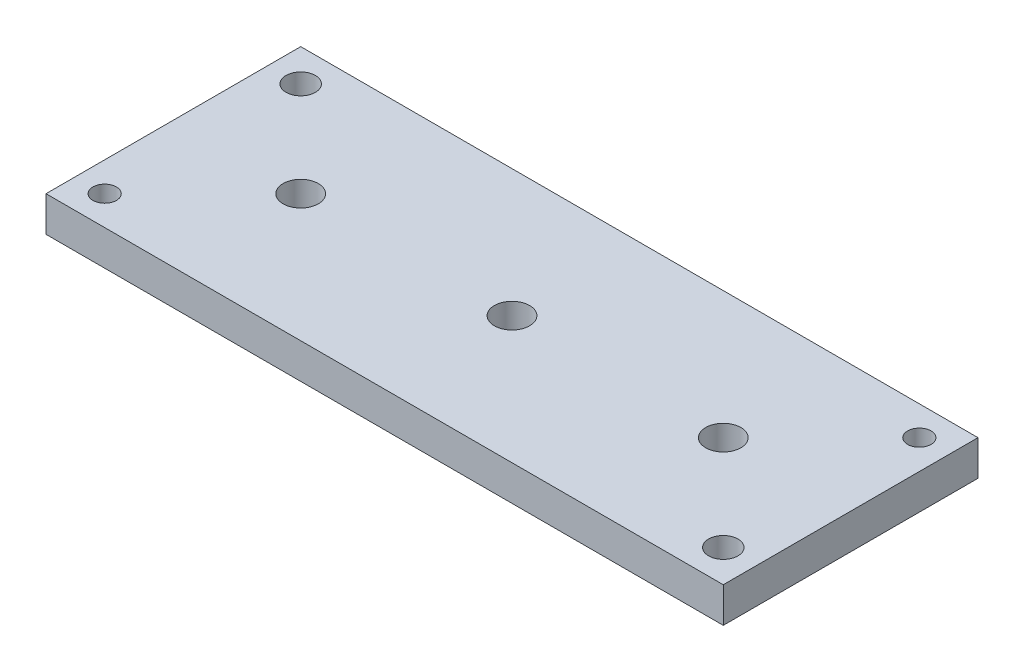
SolidWorks part; units mm, degrees
ref_plane "Front" through (0, 0, 0) normal (0, 0, 1) x (1, 0, 0)
ref_plane "Top" through (0, 0, 0) normal (0, 1, 0) x (1, 0, 0)
ref_plane "Right" through (0, 0, 0) normal (1, 0, 0) x (0, 0, -1)
sketch "Sketch1" plane through (0, 0, 0) normal (0, 1, 0) x (1, 0, 0)
  line L1 (0, 0) -> (57.7, 0)
  line L2 (0, 0) -> (0, 21.7)
  line L3 (0, 21.7) -> (57.7, 21.7)
  line L4 (57.7, 0) -> (57.7, 21.7)
  dimension "D1" = 21.7
  dimension "D2" = 57.7
extrude "Boss-Extrude1" add sketch "Sketch1" along normal blind 2
sketch "Sketch2" plane through (0, 2, 0) normal (0, 1, 0) x (1, 0, 0)
  line L0 (1.5, 20.2) -> (1.5, 1.5)
  line L1 (0, 21.7) -> (57.7, 21.7)
  line L2 (0, 21.7) -> (0, 0)
  line L3 (0, 0) -> (57.7, 0)
  line L4 (57.7, 21.7) -> (57.7, 0)
  line L5 (1.5, 1.5) -> (56.2, 1.5)
  line L6 (56.2, 20.2) -> (56.2, 1.5)
  line L7 (1.5, 20.2) -> (56.2, 20.2)
  dimension "D1" = 1.5
extrude "Boss-Extrude2" add sketch "Sketch2" along normal blind 75
fillet "Fillet1" radius 8 4 edges at (56.2, 39.5, -1.5) (56.2, 39.5, -20.2) (1.5, 39.5, -1.5) (1.5, 39.5, -20.2)
sketch "Sketch3" plane through (0, 77, 0) normal (0, 1, 0) x (1, 0, 0)
  line L0 (1.5, 12.2) -> (1.5, 9.5) construction
  line L1 (40.0836, 20.2) -> (1.5, 20.2)
  line L2 (40.0836, 20.2) -> (40.0836, 17.7)
  line L3 (40.0836, 17.7) -> (1.5, 17.7)
  line L4 (1.5, 20.2) -> (1.5, 17.7)
  line L6 (48.2, 20.2) -> (9.5, 20.2) construction
  dimension "D1" = 2.5
extrude "Cut-Extrude1" cut sketch "Sketch3" against normal up to surface (75 mm away) up to face at (28.85, 2, -10.85)
sketch "Sketch4" plane through (0, 77, 0) normal (0, 1, 0) x (1, 0, 0)
  line L0 (9.5, 1.5) -> (48.2, 1.5) construction
  line L1 (39.1106, 1.5) -> (56.2, 1.5)
  line L2 (39.1106, 1.5) -> (39.1106, 4)
  line L3 (39.1106, 4) -> (56.2, 4)
  line L4 (56.2, 1.5) -> (56.2, 4)
  dimension "D1" = 2.5
extrude "Cut-Extrude2" cut sketch "Sketch4" against normal blind 75
sketch "Sketch5" plane through (0, 77, 0) normal (0, 1, 0) x (1, 0, 0)
  line L0 (57.7, 21.7) -> (0, 21.7) construction
  line L1 (57.7, 0) -> (57.7, 21.7) construction
  line L2 (0, 21.7) -> (0, 0) construction
  line L3 (0, 0) -> (57.7, 0) construction
  circle A0 centre (55.2, 19.2) radius 1
  circle A1 centre (2.5, 2.5) radius 1
  dimension "D1" = 2
  dimension "D2" = 2
  dimension "D3" = 2.5
  dimension "D4" = 2.5
  dimension "D5" = 2.5
  dimension "D6" = 2.5
extrude "Cut-Extrude3" cut sketch "Sketch5" against normal blind 8
sketch "Sketch6" plane through (0, 77, 0) normal (0, 1, 0) x (1, 0, 0)
  line L0 (48.2, 20.2) -> (1.5, 20.2) construction
  line L1 (0, 21.7) -> (57.7, 21.7)
  line L2 (0, 21.7) -> (0, 0)
  line L3 (0, 0) -> (57.7, 0)
  line L4 (57.7, 21.7) -> (57.7, 0)
  line L5 (1.5, 17.7) -> (3.6905, 17.7) construction
  line L6 (1.5, 20.2) -> (1.5, 17.7) construction
  line L7 (56.2, 4) -> (54.0095, 4) construction
  line L8 (9.5, 1.5) -> (56.2, 1.5) construction
  line L9 (56.2, 1.5) -> (56.2, 4) construction
  circle A0 centre (2.5, 2.5) radius 1
  circle A1 centre (55.2, 19.2) radius 1
  circle A2 centre (2.75, 18.95) radius 1.25
  circle A3 centre (54.95, 2.75) radius 1.25
extrude "Boss-Extrude3" add sketch "Sketch6" along normal blind 3
sketch "Sketch7" plane through (0, 80, 0) normal (0, 1, 0) x (1, 0, 0)
  line L0 (57.7, 10.85) -> (46.85, 10.85)
  line L1 (57.7, 0) -> (57.7, 21.7) construction
  line L2 (46.85, 10.85) -> (28.85, 10.85)
  line L3 (28.85, 10.85) -> (10.85, 10.85)
  line L4 (10.85, 10.85) -> (0, 10.85)
  line L5 (0, 21.7) -> (0, 0) construction
  circle A0 centre (10.85, 10.85) radius 1.5
  circle A1 centre (28.85, 10.85) radius 1.5
  circle A2 centre (46.85, 10.85) radius 1.5
  dimension "D1" = 3
  dimension "D2" = 3
  dimension "D3" = 3
  dimension "D4" = 18
  dimension "D5" = 18
extrude "Cut-Extrude4" cut sketch "Sketch7" against normal blind 3 contours L3 A0 L4 | L4 A0 L3 | L2 A1 L3 | L3 A1 L2 | L0 A2 L2 | L2 A2 L0
sketch "Sketch8" plane through (0, 0, 0) normal (0, -1, 0) x (1, 0, 0)
  circle A0 centre (10.85, -10.85) radius 1.5
  circle A1 centre (28.85, -10.85) radius 1.5
  circle A2 centre (46.85, -10.85) radius 1.5
extrude "Cut-Extrude5" cut sketch "Sketch8" against normal blind 3
sketch "Sketch9" plane through (0, 0, -21.7) normal (0, 0, -1) x (-1, 0, 0)
  line L0 (-57.7, 80) -> (0, 80) construction
  line L1 (-70.5299, 77) -> (21.4609, 77)
  line L2 (-70.5299, 77) -> (-70.5299, -21.3779)
  line L3 (-70.5299, -21.3779) -> (21.4609, -21.3779)
  line L4 (21.4609, 77) -> (21.4609, -21.3779)
  dimension "D1" = 3
extrude "Cut-Extrude7" cut sketch "Sketch9" against normal blind 69
